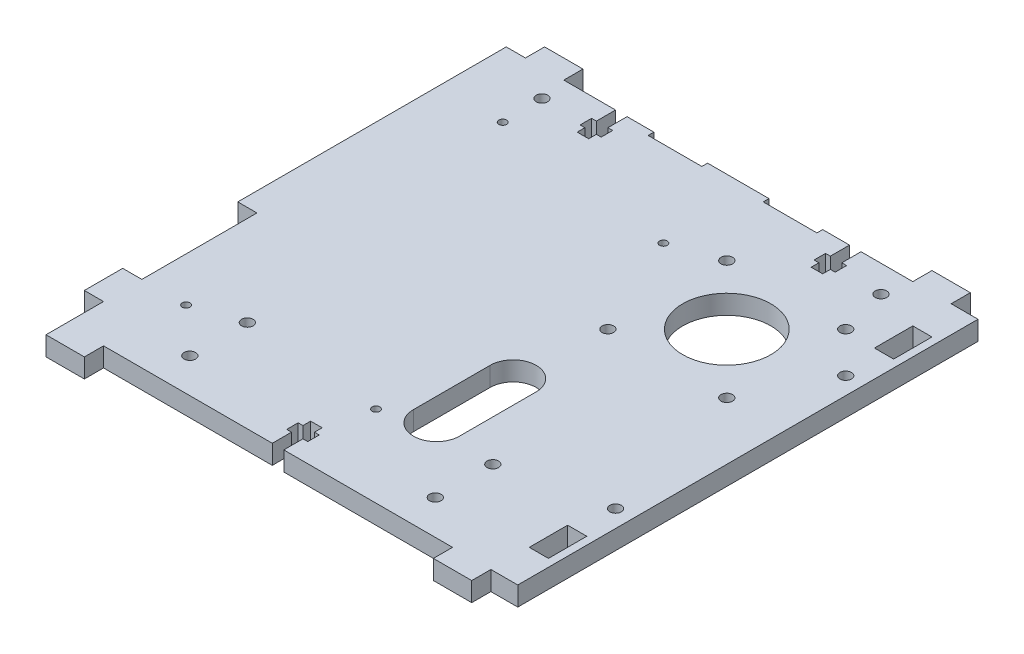
SolidWorks part; units mm, degrees
material "Maple"
ref_plane "Front Plane" through (0, 0, 0) normal (0, 0, 1) x (1, 0, 0)
ref_plane "Top Plane" through (0, 0, 0) normal (0, 1, 0) x (1, 0, 0)
ref_plane "Right Plane" through (0, 0, 0) normal (1, 0, 0) x (0, 0, -1)
sketch "Sketch2" plane through (0, 0, 0) normal (0, 1, 0) x (1, 0, 0)
  line L0 (-13, 100.5) -> (-44, 69.5) construction
  line L1 (0, 0) -> (-121, 0)
  line L2 (0, 0) -> (0, 120)
  line L3 (0, 120) -> (-121, 120)
  line L4 (-121, 0) -> (-121, 120)
  line L5 (-44, 100.5) -> (-13, 100.5) construction
  line L6 (-44, 100.5) -> (-44, 69.5) construction
  line L7 (-44, 69.5) -> (-13, 69.5) construction
  line L8 (-13, 100.5) -> (-13, 69.5) construction
  line L9 (-92.5, 39) -> (-28.5, 39) construction
  line L10 (0, 60) -> (-21.1012, 60) construction
  line L11 (-28.5, 100.5) -> (-28.5, 120) construction
  line L12 (-28.5, 39) -> (-28.5, 85) construction
  line L13 (-60.5, 39) -> (-60.5, 0) construction
  line L14 (-53.66, 6) -> (-107, 6) construction
  line L15 (-107, 6) -> (-107, 107.6) construction
  line L16 (-107, 107.6) -> (-53.66, 107.6) construction
  line L17 (-53.66, 107.6) -> (-53.66, 6) construction
  circle A0 centre (-28.5, 85) radius 11.5
  circle A1 centre (-44, 100.5) radius 1.5
  circle A2 centre (-13, 100.5) radius 1.5
  circle A3 centre (-13, 69.5) radius 1.5
  circle A4 centre (-44, 69.5) radius 1.5
  circle A5 centre (-92.5, 39) radius 4 construction
  circle A6 centre (-28.5, 39) radius 4 construction
  circle A7 centre (-92.5, 24) radius 1.5
  circle A8 centre (-92.5, 9) radius 1.5
  circle A9 centre (-28.5, 9) radius 1.5
  circle A10 centre (-28.5, 24) radius 1.5
  circle A11 centre (-104.46, 19.97) radius 1
  circle A12 centre (-104.46, 102.52) radius 1
  circle A13 centre (-56.2, 96.17) radius 1
  circle A14 centre (-56.2, 21.24) radius 1
  point P49 (-60.5, 0)
  dimension "D1" = 23
  dimension "D2" = 3
  dimension "D4" = 8
  dimension "D12" = 3
  dimension "D21" = 2
  dimension "D3" = 31
  dimension "D5" = 64
  dimension "D6" = 46
  dimension "D7" = 14
  dimension "D8" = 21
  dimension "D9" = 120
  dimension "D10" = 121
  dimension "D11" = 6
  dimension "D13" = 30
  dimension "D14" = 15
  dimension "D15" = 101.6
  dimension "D16" = 53.34
  dimension "D17" = 2.54
  dimension "D19" = 50.8
  dimension "D22" = 13.97
  dimension "D23" = 15.24
  dimension "D24" = 96.52
  dimension "D25" = 90.17
extrude "Boss-Extrude1" add sketch "Sketch2" along normal blind 5
sketch "Sketch3" plane through (0, 5, 0) normal (0, 1, 0) x (1, 0, 0)
  line L0 (0, 120) -> (-121, 120) construction
  line L1 (-116, 120) -> (-106, 120)
  line L2 (-116, 120) -> (-116, 125)
  line L3 (-116, 125) -> (-106, 125)
  line L4 (-106, 120) -> (-106, 125)
  line L5 (-15, 120) -> (-5, 120)
  line L6 (-15, 120) -> (-15, 125)
  line L7 (-15, 125) -> (-5, 125)
  line L8 (-5, 120) -> (-5, 125)
  line L9 (-121, 60) -> (-141.3828, 60) construction
  line L10 (-121, 120) -> (-121, 0) construction
  line L11 (-5, 0) -> (-5, -5)
  line L12 (-15, -5) -> (-5, -5)
  line L13 (-15, 0) -> (-15, -5)
  line L14 (-15, 0) -> (-5, 0)
  line L15 (-106, 0) -> (-106, -5)
  line L16 (-116, -5) -> (-106, -5)
  line L17 (-116, 0) -> (-116, -5)
  line L18 (-116, 0) -> (-106, 0)
  line L20 (0, 120) -> (2, 120)
  line L21 (0, 120) -> (0, 0)
  line L22 (0, 0) -> (2, 0)
  line L23 (2, 120) -> (2, 0)
  dimension "D1" = 5
  dimension "D2" = 5
  dimension "D3" = 10
  dimension "D4" = 2
  dimension "D5" = 5
extrude "Boss-Extrude2" add sketch "Sketch3" against normal up to surface (5 mm away) up to face at (-60.5, 0, -60)
sketch "Sketch4" plane through (0, 5, 0) normal (0, 1, 0) x (1, 0, 0)
  line L0 (2, 120) -> (-5, 120) construction
  line L1 (0, 110) -> (-5, 110)
  line L2 (0, 110) -> (0, 100)
  line L3 (0, 100) -> (-5, 100)
  line L4 (-5, 110) -> (-5, 100)
  line L5 (0, 10) -> (-5, 10)
  line L6 (0, 10) -> (0, 20)
  line L7 (0, 20) -> (-5, 20)
  line L8 (-5, 10) -> (-5, 20)
  line L9 (2, 0) -> (2, 120) construction
  line L10 (-5, 0) -> (2, 0) construction
  line L11 (-60.5, 0) -> (-60.5, 120) construction
  line L12 (-106, 0) -> (-15, 0) construction
  line L13 (2, 60) -> (-121, 60) construction
  line L14 (-121, 120) -> (-121, 0) construction
  line L15 (-121, 50) -> (-116, 50)
  line L16 (-121, 50) -> (-121, 20)
  line L17 (-121, 20) -> (-116, 20)
  line L18 (-116, 50) -> (-116, 20)
  line L19 (-2.5, 90) -> (-2.5, 100) construction
  line L20 (-116, 0) -> (-121, 0)
  line L21 (-15, 120) -> (-106, 120) construction
  line L22 (-116, 0) -> (-116, 10)
  line L23 (-116, 10) -> (-121, 10)
  line L24 (-121, 0) -> (-121, 10)
  line L25 (-16.3, 113) -> (-60.5, 113) construction
  line L26 (-82.5, 120) -> (-82.5, 118.5)
  line L27 (-52.5, 120) -> (-38.5, 120)
  line L28 (-52.5, 120) -> (-52.5, 118.5)
  line L29 (-52.5, 118.5) -> (-38.5, 118.5)
  line L30 (-38.5, 120) -> (-38.5, 118.5)
  line L31 (-68.5, 118.5) -> (-82.5, 118.5)
  line L32 (-68.5, 120) -> (-68.5, 118.5)
  line L33 (-68.5, 120) -> (-82.5, 120)
  line L34 (-31.5, 120) -> (-31.5, 115)
  line L35 (-31.5, 115) -> (-32.75, 115)
  line L36 (-32.75, 115) -> (-32.75, 112)
  line L37 (-32.75, 112) -> (-31.5, 112)
  line L38 (-31.5, 112) -> (-31.5, 110)
  line L39 (-31.5, 110) -> (-28.5, 110)
  line L40 (-28.5, 110) -> (-28.5, 112)
  line L41 (-28.5, 112) -> (-27.25, 112)
  line L42 (-27.25, 112) -> (-27.25, 115)
  line L43 (-27.25, 115) -> (-28.5, 115)
  line L44 (-28.5, 115) -> (-28.5, 120)
  line L45 (-28.5, 120) -> (-31.5, 120)
  line L46 (-92.5, 120) -> (-89.5, 120)
  line L47 (-92.5, 115) -> (-92.5, 120)
  line L48 (-93.75, 115) -> (-92.5, 115)
  line L49 (-93.75, 112) -> (-93.75, 115)
  line L50 (-92.5, 112) -> (-93.75, 112)
  line L51 (-92.5, 110) -> (-92.5, 112)
  line L52 (-89.5, 110) -> (-92.5, 110)
  line L53 (-89.5, 112) -> (-89.5, 110)
  line L54 (-88.25, 112) -> (-89.5, 112)
  line L55 (-88.25, 115) -> (-88.25, 112)
  line L56 (-89.5, 115) -> (-88.25, 115)
  line L57 (-89.5, 120) -> (-89.5, 115)
  line L58 (-45.2, 26) -> (-45.2, 46) construction
  line L59 (-51.2, 26) -> (-51.2, 46)
  line L60 (-39.2, 26) -> (-39.2, 46)
  line L61 (-62, 0) -> (-62, 5)
  line L62 (-62, 5) -> (-63.25, 5)
  line L63 (-63.25, 5) -> (-63.25, 8)
  line L64 (-63.25, 8) -> (-62, 8)
  line L65 (-62, 8) -> (-62, 10)
  line L66 (-62, 10) -> (-59, 10)
  line L67 (-62, 0) -> (-59, 0)
  line L68 (-59, 8) -> (-59, 10)
  line L69 (-57.75, 8) -> (-59, 8)
  line L70 (-57.75, 5) -> (-57.75, 8)
  line L71 (-59, 5) -> (-57.75, 5)
  line L72 (-59, 0) -> (-59, 5)
  circle A0 centre (-2.5, 90) radius 1.5
  circle A1 centre (-2.5, 30) radius 1.5
  circle A2 centre (-16.3, 113) radius 1.5
  circle A3 centre (-104.7, 113) radius 1.5
  arc A4 (-51.2, 26) -> (-39.2, 26) centre (-45.2, 26) ccw
  arc A5 (-39.2, 46) -> (-51.2, 46) centre (-45.2, 46) ccw
  circle A6 centre (-56.2, 21.24) radius 1 construction
  point P12 (-2.5, 10)
  point P55 (-30, 120)
  point P67 (-45.2, 36)
  point P87 (-45.2, 20)
  point P97 (-60.5, 10)
  dimension "D9" = 3
  dimension "D12" = 3
  dimension "D23" = 5
  dimension "D1" = 10
  dimension "D2" = 10
  dimension "D3" = 5
  dimension "D4" = 2
  dimension "D5" = 10
  dimension "D6" = 50
  dimension "D7" = 10
  dimension "D8" = 10
  dimension "D10" = 30
  dimension "D11" = 7
  dimension "D13" = 44.2
  dimension "D14" = 1.5
  dimension "D15" = 14
  dimension "D16" = 22
  dimension "D17" = 3
  dimension "D18" = 2
  dimension "D19" = 5
  dimension "D20" = 5.5
  dimension "D21" = 3
  dimension "D22" = 30.5
  dimension "D24" = 20
  dimension "D25" = 12
  dimension "D26" = 20
  dimension "D27" = 3
extrude "Cut-Extrude1" cut sketch "Sketch4" against normal through all
